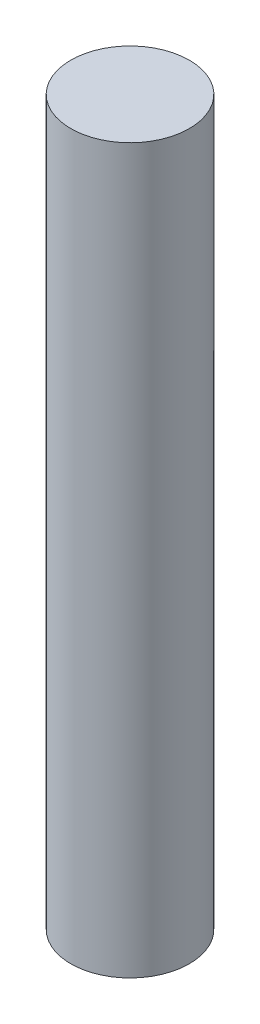
SolidWorks part; units mm, degrees
material "1023 Carbon Steel Sheet (SS)"
ref_plane "Front Plane" through (0, 0, 0) normal (0, 0, 1) x (1, 0, 0)
ref_plane "Top Plane" through (0, 0, 0) normal (0, 1, 0) x (1, 0, 0)
ref_plane "Right Plane" through (0, 0, 0) normal (1, 0, 0) x (0, 0, -1)
other "Center of Mass"
sketch "Sketch1" plane through (0, 0, 0) normal (0, 1, 0) x (1, 0, 0)
  circle A0 centre (0, 0) radius 10
  dimension "D1" = 20
extrude "Boss-Extrude1" add sketch "Sketch1" along normal mid plane 122
equation "\"test\"= \"SW-Density\""
